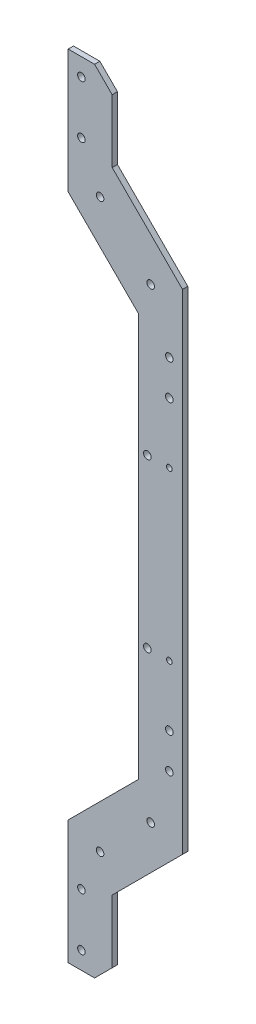
SolidWorks part; units mm, degrees
material "Thornel Mat VMA"
ref_plane "前视基准面" through (0, 0, 0) normal (0, 0, 1) x (1, 0, 0)
ref_plane "上视基准面" through (0, 0, 0) normal (0, 1, 0) x (1, 0, 0)
ref_plane "右视基准面" through (0, 0, 0) normal (1, 0, 0) x (0, 0, -1)
sketch "Sketch1" plane through (0, 0, 0) normal (0, 0, 1) x (1, 0, 0)
  line L3 (-322.7002, -118.7868) -> (-372.7002, -168.7868) construction
  line L4 (-307.7002, -125) -> (-307.7002, 125) construction
  line L7 (-357.7002, 279) -> (-357.7002, 175) construction
  line L8 (-372.7002, 294) -> (-372.7002, 168.7868) construction
  line L9 (-322.7002, 118.7868) -> (-372.7002, 168.7868) construction
  line L11 (-372.7002, -168.7868) -> (-372.7002, -225)
  line L13 (-332.7002, -128.7868) -> (-372.7002, -168.7868)
  line L14 (-307.7002, -125) -> (-307.7002, 125)
  line L18 (-372.7002, 225) -> (-372.7002, 168.7868)
  line L19 (-332.7002, 128.7868) -> (-372.7002, 168.7868)
  line L20 (-372.7002, 225) -> (-357.7002, 225)
  line L22 (-372.7002, -225) -> (-357.7002, -225)
  line L23 (-332.7002, 128.7868) -> (-332.7002, -128.7868)
  line L24 (-357.7002, 225) -> (-347.7002, 225)
  line L25 (-347.7002, 225) -> (-347.7002, 179.1421)
  line L26 (-347.7002, 179.1421) -> (-307.7002, 139.1421)
  line L27 (-307.7002, 139.1421) -> (-307.7002, 125)
  line L28 (-307.7002, 0) -> (-165.6245, 0) construction
  line L29 (-307.7002, -139.1421) -> (-307.7002, -125)
  line L30 (-347.7002, -179.1421) -> (-307.7002, -139.1421)
  line L31 (-347.7002, -225) -> (-347.7002, -179.1421)
  line L32 (-357.7002, -225) -> (-347.7002, -225)
  line L33 (-372.7002, -225) -> (-357.7002, -225)
  line L34 (-332.7002, -128.7868) -> (-372.7002, -168.7868)
  line L35 (-372.7002, -225) -> (-372.7002, -168.7868)
  dimension "D2" = 50
extrude "Boss-Extrude1" add sketch "Sketch1" along normal blind 3 contours L22 L32 L31 L30 L29 L14 L27 L26 L25 L24 L20 L18 L19 L23 L13 L11
sketch "Sketch2" plane through (0, 0, 3) normal (0, 0, 1) x (1, 0, 0)
  line L0 (-372.7002, 168.7868) -> (-372.7002, 154.6447)
  line L1 (-372.7002, 154.6447) -> (-332.7002, 114.6447)
  line L2 (-332.7002, 128.7868) -> (-332.7002, -128.7868) construction
  line L3 (-372.7002, -168.7868) -> (-372.7002, -154.6447)
  line L4 (-372.7002, -154.6447) -> (-332.7002, -114.6447)
  line L5 (-332.7002, -128.7868) -> (-372.7002, -168.7868) construction
  line L6 (-332.7002, 128.7868) -> (-372.7002, 168.7868) construction
  line L7 (-372.7002, 168.7868) -> (-332.7002, 128.7868)
  line L8 (-332.7002, 128.7868) -> (-332.7002, 114.6447)
  line L9 (-332.7002, -114.6447) -> (-332.7002, -128.7868)
  line L10 (-332.7002, -128.7868) -> (-372.7002, -168.7868)
  dimension "D1" = 10
  dimension "D2" = 10
extrude "Boss-Extrude2" add sketch "Sketch2" against normal up to vertex (3 mm away) up to point (-372.7002, 168.7868, 0)
chamfer "Chamfer1" distance 10 angle 45 2 edges at (-347.7002, -225, 1.5) (-347.7002, 225, 1.5)
sketch "Sketch3" plane through (0, 0, 3) normal (0, 0, 1) x (1, 0, 0)
  circle A0 centre (-327.7002, 47.5) radius 2.15
  circle A1 centre (-315.2002, 47.5) radius 1.6
  circle A2 centre (-327.7002, -47.5) radius 2.15
  circle A3 centre (-315.2002, -47.5) radius 1.6
extrude "Cut-Extrude1" cut sketch "Sketch3" against normal blind 10
sketch "Sketch4" plane through (0, 0, 0) normal (0, 0, -1) x (-1, 0, 0)
  line L0 (365.2002, 225) -> (365.2002, 171.8934) construction
  line L1 (372.7002, 225) -> (357.7002, 225) construction
  line L2 (365.2002, 171.8934) -> (315.2002, 121.8934) construction
  line L3 (315.2002, 121.8934) -> (315.2002, -21.7444) construction
  line L4 (372.7002, 154.6447) -> (332.7002, 114.6447) construction
  line L5 (307.7002, -139.1421) -> (307.7002, 139.1421) construction
  line L7 (332.7002, 0) -> (239.2264, 0) construction
  line L8 (332.7002, 114.6447) -> (332.7002, -114.6447) construction
  line L9 (315.2002, -121.8934) -> (315.2002, 21.7444) construction
  line L10 (365.2002, -171.8934) -> (315.2002, -121.8934) construction
  line L11 (365.2002, -225) -> (365.2002, -171.8934) construction
  circle A0 centre (365.2002, 215) radius 2.15
  circle A1 centre (365.2002, 185) radius 2.15
  circle A2 centre (354.5936, 161.2868) radius 2.15
  circle A3 centre (325.8068, 132.5) radius 2.15
  circle A4 centre (315.2002, 101.8934) radius 2.15
  circle A5 centre (315.2002, 81.8934) radius 2.15
  circle A6 centre (315.2002, -81.8934) radius 2.15
  circle A7 centre (315.2002, -101.8934) radius 2.15
  circle A8 centre (325.8068, -132.5) radius 2.15
  circle A9 centre (354.5936, -161.2868) radius 2.15
  circle A10 centre (365.2002, -185) radius 2.15
  circle A11 centre (365.2002, -215) radius 2.15
  dimension "D3" = 4.3
  dimension "D4" = 10
  dimension "D5" = 30
  dimension "D6" = 15
  dimension "D7" = 15
  dimension "D8" = 20
  dimension "D9" = 20
  dimension "D10" = 4.3
  dimension "D1" = 17.5
  dimension "D2" = 7.5
extrude "Cut-Extrude2" cut sketch "Sketch4" against normal blind 10
